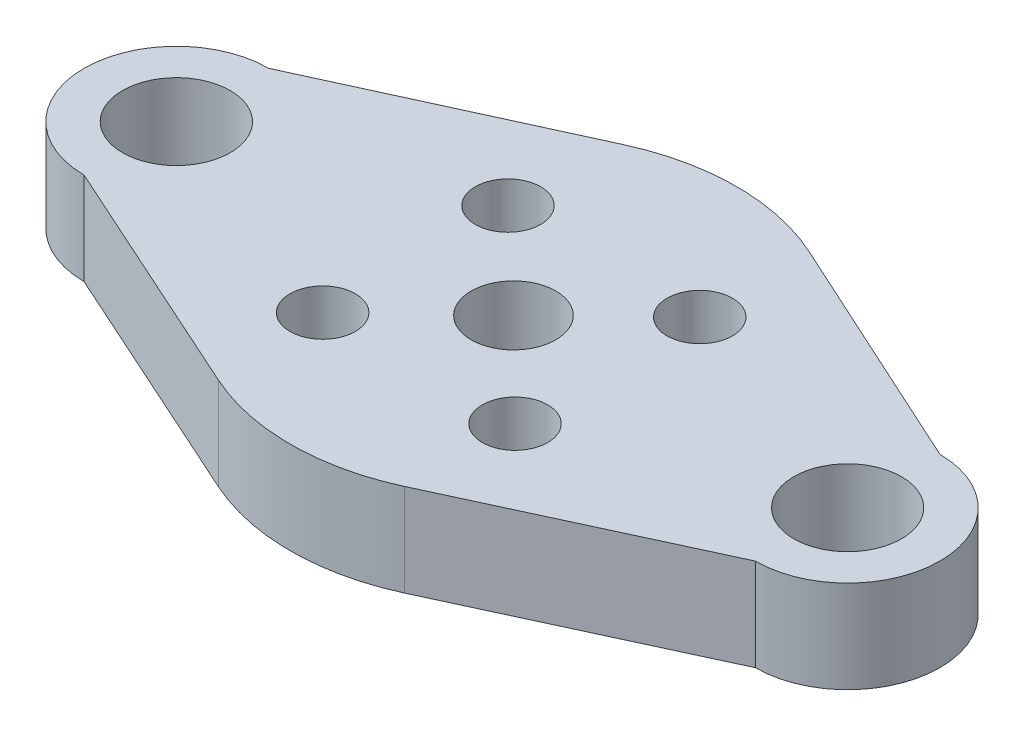
SolidWorks part; units mm, degrees
ref_plane "Plano frontal" through (0, 0, 0) normal (0, 0, 1) x (1, 0, 0)
ref_plane "Plano superior" through (0, 0, 0) normal (0, 1, 0) x (1, 0, 0)
ref_plane "Plano direito" through (0, 0, 0) normal (1, 0, 0) x (0, 0, -1)
sketch "Esboço2" plane through (0, 0, 0) normal (0, 1, 0) x (1, 0, 0)
  line L7 (-43.7089, 11.9045) -> (-12.0576, 26.3745)
  line L8 (12.0576, 26.3745) -> (43.3534, 12.067)
  line L10 (-43.7089, -12.0955) -> (-11.9258, -26.4344)
  line L11 (43.3534, -11.933) -> (12.151, -26.3316)
  circle A0 centre (-43.7089, -0.0955) radius 12
  circle A1 centre (43.3534, 0.067) radius 12
  arc A2 (-11.9258, -26.4344) -> (12.151, -26.3316) centre (0, 0) ccw
  arc A3 (12.0576, 26.3745) -> (-12.0576, 26.3745) centre (0, 0) ccw
  circle A4 centre (12.2851, 11.9176) radius 4.25
  circle A5 centre (-12.7148, 12.0007) radius 4.25
  circle A6 centre (-12.7149, -12.0824) radius 4.25
  circle A7 centre (12.2851, -12.0824) radius 4.25
  circle A8 centre (0, 0) radius 5.5
  circle A9 centre (-43.7089, -0.0955) radius 7
  circle A10 centre (43.3534, 0.067) radius 7
  dimension "D3" = 24
  dimension "D4" = 24
  dimension "D5" = 58
  dimension "D6" = 8.5
  dimension "D7" = 8.5
  dimension "D8" = 8.5
  dimension "D9" = 8.5
  dimension "D10" = 11
  dimension "D11" = 14
  dimension "D12" = 14
  dimension "D1" = 25
  dimension "D2" = 87.0625
extrude "Ressalto-extrusão2" add sketch "Esboço2" along normal blind 12 contours A0 | L8 A3 L7 A0 L10 A2 L11 A1 A8 A7 A6 A5 A4 | A1
